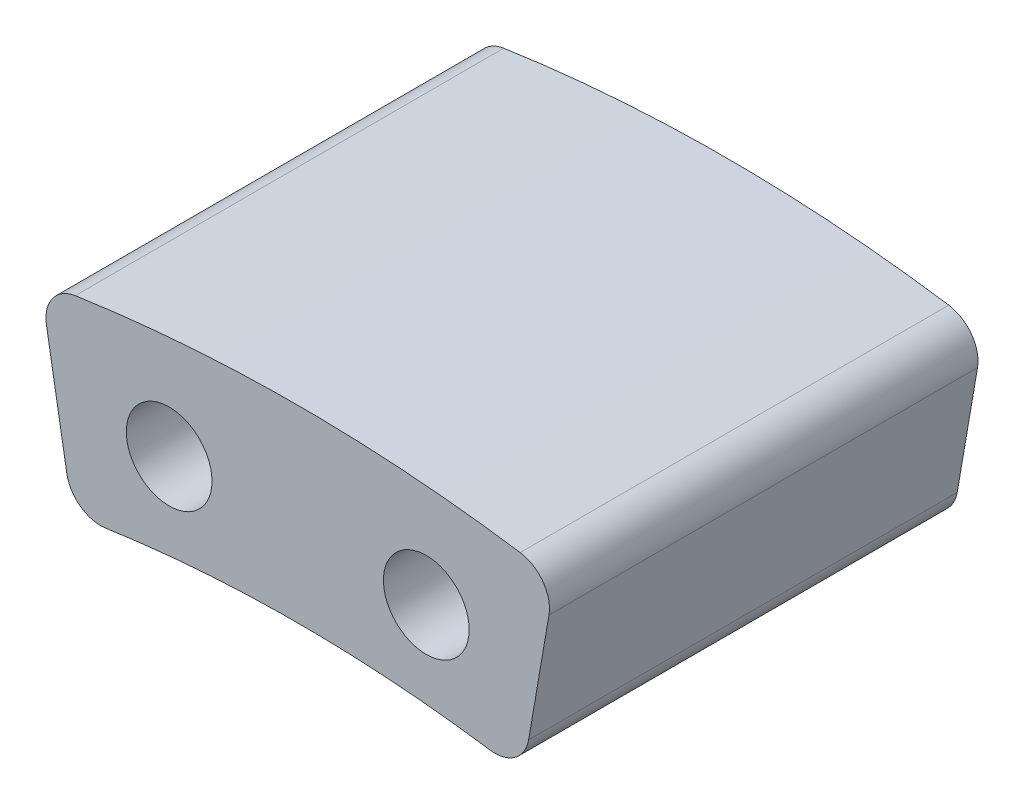
SolidWorks part; units mm, degrees
ref_plane "Front Plane" through (0, 0, 0) normal (0, 0, 1) x (1, 0, 0)
ref_plane "Top Plane" through (0, 0, 0) normal (0, 1, 0) x (1, 0, 0)
ref_plane "Right Plane" through (0, 0, 0) normal (1, 0, 0) x (0, 0, -1)
sketch "Sketch1" plane through (0, 0, 0) normal (0, 0, 1) x (1, 0, 0)
  line L0 (0, 0) -> (0, 112.395) construction
  line L1 (-19.05, 110.7688) -> (-16.6822, 97.001)
  line L2 (19.05, 110.7688) -> (16.6822, 97.001)
  arc A0 (19.05, 110.7688) -> (-19.05, 110.7688) centre (0, 0) ccw construction
  arc A1 (16.6822, 97.001) -> (-16.6822, 97.001) centre (0, 0) ccw construction
  arc A2 (19.05, 110.7688) -> (-19.05, 110.7688) centre (0, 0) ccw
  arc A3 (16.6822, 97.001) -> (-16.6822, 97.001) centre (0, 0) ccw
  circle A4 centre (0, 0) radius 104.775 construction
  circle A5 centre (9.525, 104.3411) radius 3.175
  circle A6 centre (-9.525, 104.3411) radius 3.175
  dimension "D1" = 196.85
  dimension "D2" = 224.79
  dimension "D4" = 209.55
  dimension "D5" = 6.35
  dimension "D3" = 38.1
  dimension "D6" = 19.05
extrude "Boss-Extrude1" add sketch "Sketch1" along normal blind 31.75
fillet "Fillet1" radius 2.54 4 edges at (19.05, 110.7688, 15.875) (16.6822, 97.001, 15.875) (-16.6822, 97.001, 15.875) (-19.05, 110.7688, 15.875)
